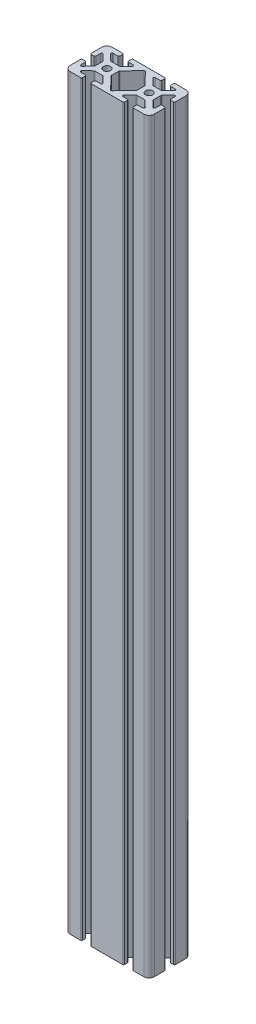
SolidWorks part; units mm, degrees
material "4032-T6"
ref_plane "Front Plane" through (0, 0, 0) normal (0, 0, 1) x (1, 0, 0)
ref_plane "Top Plane" through (0, 0, 0) normal (0, 1, 0) x (1, 0, 0)
ref_plane "Right Plane" through (0, 0, 0) normal (1, 0, 0) x (0, 0, -1)
sketch "Sketch1" plane through (0, 0, 0) normal (0, 1, 0) x (1, 0, 0)
  line L1 (5, 0) -> (75, 0)
  line L2 (0, -5) -> (0, -35)
  line L3 (5, -40) -> (75, -40)
  line L4 (80, -5) -> (80, -35)
  arc A0 (75, -40) -> (80, -35) centre (75, -35) ccw
  arc A1 (80, -5) -> (75, 0) centre (75, -5) ccw
  arc A2 (5, -40) -> (0, -35) centre (5, -35) cw
  arc A3 (0, -5) -> (5, 0) centre (5, -5) cw
  point P7 (80, -40)
  point P10 (80, 0)
  point P15 (0, 0)
  dimension "D3" = 5
  dimension "D1" = 80
  dimension "D2" = 40
extrude "Boss-Extrude1" add sketch "Sketch1" along normal blind 710 contours L3 A0 L4 A1 L1 A3 L2 A2
sketch "Sketch3" plane through (0, 710, 0) normal (0, 1, 0) x (1, 0, 0)
  line L0 (40, -2.5254) -> (40, -32.3671)
  line L1 (0, -5) -> (0, -35) construction
  line L2 (5, 0) -> (75, 0) construction
  circle A0 centre (20, -20) radius 3.4
  dimension "D4" = 6.8
  dimension "D1" = 40
  dimension "D2" = 20
  dimension "D3" = 20
extrude "Cut-Extrude1" cut sketch "Sketch3" against normal through all contours A0
ref_plane "mirro-plane" through (40, 0, 0) normal (1, 0, 0) x (0, 0, -1)
mirror "Mirror3" about plane through (40, 0, 0) normal (1, 0, 0) of "Cut-Extrude1"
ref_plane "sk5mirrorPlane" through (0, 0, 20) normal (0, 0, 1) x (1, 0, 0)
sketch "Sketch7" plane through (0, 0, 0) normal (0, -1, 0) x (-1, 0, 0)
  line L2 (-5, -40) -> (-75, -40) construction
  line L4 (-15.9, -40) -> (-24.1, -40)
  line L8 (-15.9, -40) -> (-15.9, -36.5)
  line L12 (-16.3092, -27.8) -> (-23.6908, -27.8)
  line L23 (-10.5103, -35.5) -> (-14.9, -35.5)
  line L25 (-24.1, -40) -> (-24.1, -36.5)
  line L27 (-15.6082, -28.0868) -> (-9.8093, -33.7868)
  line L31 (-29.4898, -35.5) -> (-25.1, -35.5)
  line L43 (-24.3918, -28.0868) -> (-30.1908, -33.7868)
  arc A0 (-24.3918, -28.0868) -> (-23.6908, -27.8) centre (-23.6908, -28.8) cw
  arc A1 (-16.3092, -27.8) -> (-15.6082, -28.0868) centre (-16.3092, -28.8) cw
  arc A2 (-30.1908, -33.7868) -> (-29.4898, -35.5) centre (-29.4898, -34.5) ccw
  arc A3 (-9.8093, -33.7868) -> (-10.5103, -35.5) centre (-10.5103, -34.5) cw
  arc A4 (-25.1, -35.5) -> (-24.1, -36.5) centre (-25.1, -36.5) cw
  arc A5 (-14.9, -35.5) -> (-15.9, -36.5) centre (-14.9, -36.5) ccw
  point P96 (-24.1, -35.5)
  dimension "D17" = 0
  dimension "D18" = 1
  dimension "D8" = 12.2
extrude "Cut-Extrude2" cut sketch "Sketch7" against normal through all and the other way through all
fillet "Fillet1" radius 1 2 edges at (15.9, 355, 40) (24.1, 355, 40)
mirror "Mirror8" about plane through (40, 0, 0) normal (1, 0, 0) of "Cut-Extrude2"
fillet "Fillet2" radius 1 1 edges at (55.9, 355, 40)
fillet "Fillet3" radius 1 1 edges at (64.1, 355, 40)
sketch "Sketch9" plane through (0, 0, 0) normal (0, 1, 0) x (1, 0, 0)
  line L1 (14.8998, -4.5007) -> (10.4505, -4.5007)
  line L3 (24.0998, -3.5) -> (24.1, 0)
  line L4 (15.8998, -3.5008) -> (15.9, 0)
  line L5 (15.9, 0) -> (24.1, 0)
  line L6 (16.1497, -12.2) -> (23.8503, -12.2)
  line L7 (5, 0) -> (75, 0) construction
  line L8 (25.0998, -4.5) -> (29.5503, -4.5)
  line L12 (9.7434, -6.2078) -> (15.4426, -11.9071)
  line L16 (24.5574, -11.9071) -> (30.2574, -6.2071)
  arc A0 (15.8998, -3.5008) -> (14.8998, -4.5007) centre (14.8998, -3.5007) cw
  arc A1 (24.0998, -3.5) -> (25.0998, -4.5) centre (25.0998, -3.5) ccw
  arc A2 (29.5503, -4.5) -> (30.2574, -6.2071) centre (29.5503, -5.5) cw
  arc A3 (24.5574, -11.9071) -> (23.8503, -12.2) centre (23.8503, -11.2) cw
  arc A4 (9.7434, -6.2078) -> (10.4505, -4.5007) centre (10.4505, -5.5007) cw
  arc A5 (15.4426, -11.9071) -> (16.1497, -12.2) centre (16.1497, -11.2) ccw
  dimension "D2" = 1
  dimension "D1" = 0
  dimension "D5" = 12.2
  dimension "D6" = 4.5
extrude "Cut-Extrude3" cut sketch "Sketch9" along normal through all
mirror "Mirror9" about plane through (40, 0, 0) normal (1, 0, 0) of "Cut-Extrude3"
sketch "Sketch10" plane through (0, 0, 0) normal (0, 1, 0) x (1, 0, 0)
  line L0 (4.5, -14.9) -> (4.5, -10.5861)
  line L4 (0, -24.1) -> (3.5, -24.1)
  line L5 (0, -15.9) -> (3.5, -15.9)
  line L8 (12.2, -23.4919) -> (12.2, -16.5081)
  line L10 (0, -5) -> (0, -35) construction
  line L13 (4.5, -29.4139) -> (4.5, -25.1)
  line L25 (11.9205, -24.1853) -> (6.2205, -30.1074)
  line L26 (11.9205, -15.8147) -> (6.2205, -9.8926)
  line L29 (0, -24.1) -> (0, -15.9)
  arc A0 (4.5, -14.9) -> (3.5, -15.9) centre (3.5, -14.9) cw
  arc A1 (3.5, -24.1) -> (4.5, -25.1) centre (3.5, -25.1) cw
  arc A2 (6.2205, -9.8926) -> (4.5, -10.5861) centre (5.5, -10.5861) ccw
  arc A3 (11.9205, -15.8147) -> (12.2, -16.5081) centre (11.2, -16.5081) cw
  arc A4 (11.9205, -24.1853) -> (12.2, -23.4919) centre (11.2, -23.4919) ccw
  arc A5 (4.5, -29.4139) -> (6.2205, -30.1074) centre (5.5, -29.4139) ccw
  dimension "D3" = 1
  dimension "D7" = 12.2
  dimension "D9" = 4.5
  dimension "D17" = 0
extrude "Cut-Extrude4" cut sketch "Sketch10" along normal through all
fillet "Fillet4" radius 1 1 edges at (24.1, 355, 0)
fillet "Fillet5" radius 1 1 edges at (64.1, 355, 0)
fillet "Fillet6" radius 1 1 edges at (55.9, 355, 0)
fillet "Fillet7" radius 1 1 edges at (15.9, 355, 0)
fillet "Fillet8" radius 1 1 edges at (0, 355, 24.1)
fillet "Fillet9" radius 1 1 edges at (0, 355, 15.9)
sketch "Sketch11" plane through (0, 0, 0) normal (0, 1, 0) x (1, 0, 0)
  line L0 (75.5, -29.6797) -> (75.5, -25.1)
  line L1 (80, -5) -> (80, -35) construction
  line L2 (67.5, -16.0953) -> (67.5, -23.9047)
  line L5 (75.5, -14.9) -> (75.5, -10.3203)
  line L7 (80, -24.1) -> (80, -15.9)
  line L8 (80, -5) -> (80, -35) construction
  line L13 (113.5168, -27.8) -> (113.5178, -27.6385)
  line L17 (67.8065, -15.3748) -> (73.8065, -9.5998)
  line L63 (67.8065, -24.6252) -> (73.8065, -30.4002)
  line L66 (76.5, -15.9) -> (80, -15.9)
  line L68 (76.5, -24.1) -> (80, -24.1)
  arc A44 (75.5, -25.1) -> (76.5, -24.1) centre (76.5, -25.1) cw
  arc A45 (75.5, -14.9) -> (76.5, -15.9) centre (76.5, -14.9) ccw
  arc A46 (73.8065, -9.5998) -> (75.5, -10.3203) centre (74.5, -10.3203) cw
  arc A47 (73.8065, -30.4002) -> (75.5, -29.6797) centre (74.5, -29.6797) ccw
  arc A48 (67.8065, -24.6252) -> (67.5, -23.9047) centre (68.5, -23.9047) cw
  arc A49 (67.8065, -15.3748) -> (67.5, -16.0953) centre (68.5, -16.0953) ccw
  dimension "D3" = 1
  dimension "D2" = 4.5
  dimension "D4" = 12.5
ref_plane "offset1" through (60, 0, 0) normal (1, 0, 0) x (0, 0, -1)
mirror "Mirror10" about plane through (40, 0, 0) normal (1, 0, 0) of "Cut-Extrude4"
fillet "Fillet10" radius 1 1 edges at (80, 355, 15.9)
fillet "Fillet11" radius 1 1 edges at (80, 355, 24.1)
mirror "Mirror11" about plane through (60, 0, 0) normal (1, 0, 0) of "Mirror10"
ref_plane "Plane2" through (20, 0, 0) normal (-1, 0, 0) x (0, 0, 1)
mirror "Mirror12" about plane through (20, 0, 0) normal (-1, 0, 0) of "Cut-Extrude4"
sketch "Sketch12" plane through (0, 0, 0) normal (0, -1, 0) x (-1, 0, 0)
  line L0 (-28.0795, -24.1853) -> (-39.3271, -35.8711)
  line L2 (-51.9226, -24.2109) -> (-40.7702, -35.8689)
  line L4 (-39.2795, -4.1783) -> (-28.0795, -15.8147)
  line L7 (-51.9205, -15.8147) -> (-40.7205, -4.1783)
  line L8 (-27.8, -23.4919) -> (-27.8, -16.5081)
  line L9 (-52.2, -23.5196) -> (-52.2, -16.5081)
  line L10 (-52.2, -23.4919) -> (-52.2, -16.5081) construction
  line L11 (-27.8, -23.4919) -> (-27.8, -16.5081) construction
  arc A0 (-39.2795, -4.1783) -> (-40.7205, -4.1783) centre (-40, -4.8718) ccw
  arc A1 (-39.3271, -35.8711) -> (-40.7702, -35.8689) centre (-40.0476, -35.1776) cw
  arc A2 (-51.9205, -15.8147) -> (-52.2, -16.5081) centre (-51.2, -16.5081) ccw
  arc A3 (-52.2, -23.5196) -> (-51.9226, -24.2109) centre (-51.2, -23.5196) ccw
  arc A4 (-28.0795, -15.8147) -> (-27.8, -16.5081) centre (-28.8, -16.5081) cw
  arc A5 (-27.8, -23.4919) -> (-28.0795, -24.1853) centre (-28.8, -23.4919) cw
  dimension "D3" = 1
  dimension "D4" = 1
  dimension "D1" = 0
  dimension "D2" = 0
extrude "Cut-Extrude5" cut sketch "Sketch12" against normal blind 1000
